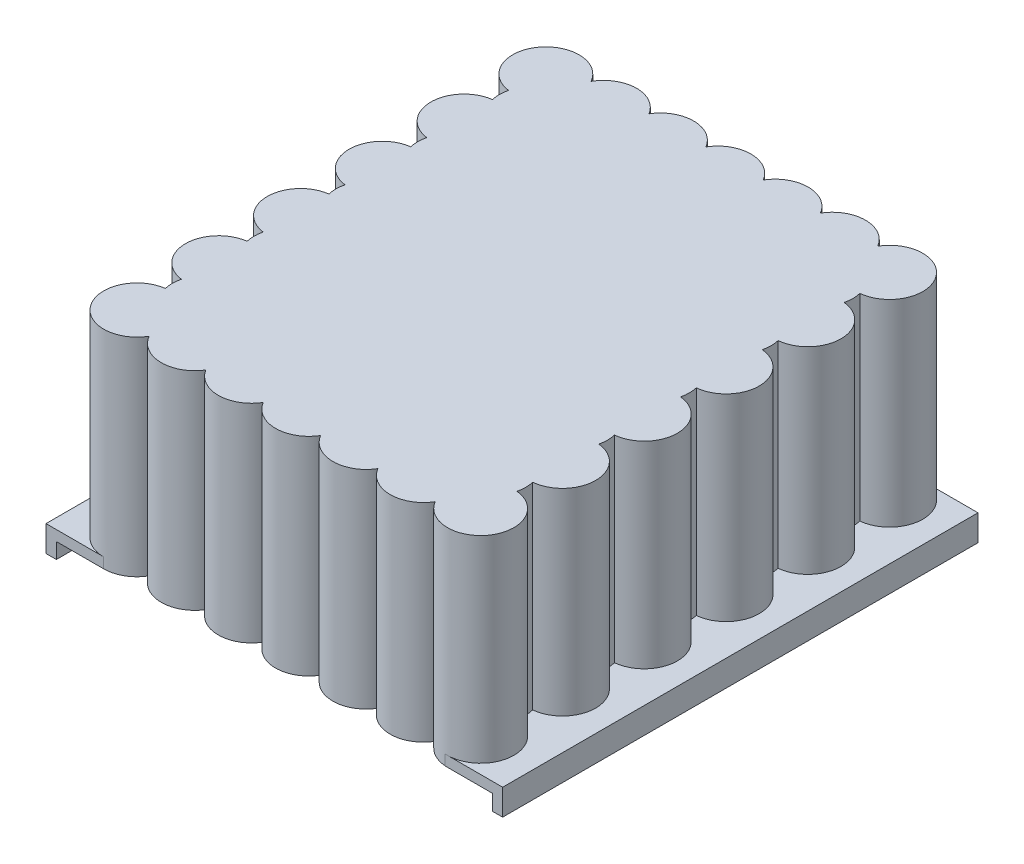
SolidWorks part; units mm, degrees
material "Titanium Ti-5Al-2.5Sn"
ref_plane "Front Plane" through (0, 0, 0) normal (0, 0, 1) x (1, 0, 0)
ref_plane "Top Plane" through (0, 0, 0) normal (0, 1, 0) x (1, 0, 0)
ref_plane "Right Plane" through (0, 0, 0) normal (1, 0, 0) x (0, 0, -1)
sketch "Sketch2" plane through (0, 0, 0) normal (0, 1, 0) x (1, 0, 0)
  circle A0 centre (-104.3845, 125.3413) radius 14
  circle A1 centre (-69.3845, 125.3413) radius 14
  circle A2 centre (-34.3845, 125.3413) radius 14
  circle A3 centre (0.6155, 125.3413) radius 14
  circle A4 centre (35.6155, 125.3413) radius 14
  circle A5 centre (70.6155, 125.3413) radius 14
  circle A6 centre (105.6155, 125.3413) radius 14
  circle A7 centre (-69.3845, 75.3413) radius 14
  circle A8 centre (-34.3845, 75.3413) radius 14
  circle A9 centre (0.6155, 75.3413) radius 14
  circle A10 centre (35.6155, 75.3413) radius 14
  circle A11 centre (70.6155, 75.3413) radius 14
  circle A12 centre (105.6155, 75.3413) radius 14
  circle A13 centre (-69.3845, 25.3413) radius 14
  circle A14 centre (-34.3845, 25.3413) radius 14
  circle A15 centre (0.6155, 25.3413) radius 14
  circle A16 centre (35.6155, 25.3413) radius 14
  circle A17 centre (70.6155, 25.3413) radius 14
  circle A18 centre (105.6155, 25.3413) radius 14
  circle A19 centre (-69.3845, -24.6587) radius 14
  circle A20 centre (-34.3845, -24.6587) radius 14
  circle A21 centre (0.6155, -24.6587) radius 14
  circle A22 centre (35.6155, -24.6587) radius 14
  circle A23 centre (70.6155, -24.6587) radius 14
  circle A24 centre (105.6155, -24.6587) radius 14
  circle A25 centre (-69.3845, -74.6587) radius 14
  circle A26 centre (-34.3845, -74.6587) radius 14
  circle A27 centre (0.6155, -74.6587) radius 14
  circle A28 centre (35.6155, -74.6587) radius 14
  circle A29 centre (70.6155, -74.6587) radius 14
  circle A30 centre (105.6155, -74.6587) radius 14
  circle A31 centre (-69.3845, -124.6587) radius 14
  circle A32 centre (-34.3845, -124.6587) radius 14
  circle A33 centre (0.6155, -124.6587) radius 14
  circle A34 centre (35.6155, -124.6587) radius 14
  circle A35 centre (70.6155, -124.6587) radius 14
  circle A36 centre (105.6155, -124.6587) radius 14
  circle A37 centre (-104.3845, 75.3413) radius 14
  circle A38 centre (-104.3845, 25.3413) radius 14
  circle A39 centre (-104.3845, -24.6587) radius 14
  circle A40 centre (-104.3845, -74.6587) radius 14
  circle A41 centre (-104.3845, -124.6587) radius 14
  circle A42 centre (-87.3845, 100.3413) radius 14
  circle A43 centre (-52.3845, 100.3413) radius 14
  circle A44 centre (-17.3845, 100.3413) radius 14
  circle A45 centre (17.6155, 100.3413) radius 14
  circle A46 centre (52.6155, 100.3413) radius 14
  circle A47 centre (87.6155, 100.3413) radius 14
  circle A48 centre (-52.3845, 50.3413) radius 14
  circle A49 centre (-17.3845, 50.3413) radius 14
  circle A50 centre (17.6155, 50.3413) radius 14
  circle A51 centre (52.6155, 50.3413) radius 14
  circle A52 centre (87.6155, 50.3413) radius 14
  circle A53 centre (-52.3845, 0.3413) radius 14
  circle A54 centre (-17.3845, 0.3413) radius 14
  circle A55 centre (17.6155, 0.3413) radius 14
  circle A56 centre (52.6155, 0.3413) radius 14
  circle A57 centre (87.6155, 0.3413) radius 14
  circle A58 centre (-52.3845, -49.6587) radius 14
  circle A59 centre (-17.3845, -49.6587) radius 14
  circle A60 centre (17.6155, -49.6587) radius 14
  circle A61 centre (52.6155, -49.6587) radius 14
  circle A62 centre (87.6155, -49.6587) radius 14
  circle A63 centre (-52.3845, -99.6587) radius 14
  circle A64 centre (-17.3845, -99.6587) radius 14
  circle A65 centre (17.6155, -99.6587) radius 14
  circle A66 centre (52.6155, -99.6587) radius 14
  circle A67 centre (87.6155, -99.6587) radius 14
  circle A68 centre (-87.3845, 50.3413) radius 14
  circle A69 centre (-87.3845, 0.3413) radius 14
  circle A70 centre (-87.3845, -49.6587) radius 14
  circle A71 centre (-87.3845, -99.6587) radius 14
sketch "Sketch3" plane through (0, 0, 0) normal (0, 1, 0) x (1, 0, 0)
  line L1 (-132.3198, 152.7914) -> (134.3802, 152.7914)
  line L2 (-132.3198, 152.7914) -> (-132.3198, -152.0086)
  line L3 (-132.3198, -152.0086) -> (134.3802, -152.0086)
  line L4 (134.3802, 152.7914) -> (134.3802, -152.0086)
  dimension "D1" = 304.8
  dimension "D2" = 266.7
extrude "Boss-Extrude1" add sketch "Sketch3" along normal blind 127
extrude "Cut-Extrude1" cut sketch "Sketch2" along normal blind 101.6
sketch "Sketch4" plane through (0, 0, 0) normal (0, -1, 0) x (1, 0, 0)
  line L1 (-132.3198, 152.0086) -> (134.3802, 152.0086)
  line L2 (-132.3198, 152.0086) -> (-132.3198, -152.7914)
  line L3 (-132.3198, -152.7914) -> (134.3802, -152.7914)
  line L4 (134.3802, 152.0086) -> (134.3802, -152.7914)
  arc A0 (-86.7752, 134.7985) -> (-107.1138, 104.5229) centre (-104.3845, 124.6587) ccw
  arc A5 (-16.7545, 114.3757) -> (-1.7647, 104.4976) centre (0.7715, 124.6587) ccw
  arc A7 (51.1245, 119.8835) -> (90.6148, 119.8357) centre (70.8755, 124.6587) ccw
  arc A8 (86.1781, 119.8771) -> (88.4015, 114.3757) centre (105.9275, 124.6587) ccw
  arc A9 (-49.6103, 79.513) -> (-51.8065, 84.9038) centre (-69.3325, 74.6207) ccw
  arc A10 (-51.8065, 84.9038) -> (-54.0268, 79.4152) centre (-34.2805, 74.6207) ccw
  arc A12 (33.3518, 54.4516) -> (33.3609, 94.791) centre (35.8235, 74.6207) ccw
  circle A13 centre (70.8755, 74.6207) radius 20.32
  arc A14 (88.4015, 84.9038) -> (88.4015, 64.3377) centre (105.9275, 74.6207) ccw
  arc A15 (-86.8585, 14.2997) -> (-84.6553, 19.7186) centre (-104.3845, 24.5827) ccw
  arc A16 (-89.0802, 29.3716) -> (-49.6012, 19.7272) centre (-69.3325, 24.5827) ccw
  arc A19 (16.071, 19.8137) -> (37.7142, 44.8146) centre (35.8235, 24.5827) ccw
  circle A20 centre (70.8755, 24.5827) radius 20.32
  arc A21 (88.4015, 34.8658) -> (88.4015, 14.2997) centre (105.9275, 24.5827) ccw
  arc A22 (-86.8585, -35.7383) -> (-86.8585, -15.1722) centre (-104.3845, -25.4553) ccw
  circle A23 centre (-69.3325, -25.4553) radius 20.32
  circle A24 centre (-34.2805, -25.4553) radius 20.32
  circle A25 centre (0.7715, -25.4553) radius 20.32
  circle A26 centre (35.8235, -25.4553) radius 20.32
  arc A27 (90.6057, -20.5953) -> (88.4015, -35.7383) centre (70.8755, -25.4553) ccw
  arc A28 (88.4015, -15.1722) -> (88.4015, -35.7383) centre (105.9275, -25.4553) ccw
  arc A29 (-86.8585, -85.7763) -> (-86.8585, -65.2102) centre (-104.3845, -75.4933) ccw
  circle A30 centre (-69.3325, -75.4933) radius 20.32
  circle A31 centre (-34.2805, -75.4933) radius 20.32
  circle A32 centre (0.7715, -75.4933) radius 20.32
  circle A33 centre (35.8235, -75.4933) radius 20.32
  circle A34 centre (70.8755, -75.4933) radius 20.32
  arc A35 (88.4015, -65.2102) -> (88.4015, -85.7763) centre (105.9275, -75.4933) ccw
  arc A36 (-84.6644, -120.6304) -> (-86.6147, -115.6754) centre (-104.3845, -125.5313) ccw
  arc A37 (-49.4244, -120.6136) -> (-88.6164, -120.7759) centre (-69.0004, -125.5313) ccw
  arc A38 (-14.5562, -120.6473) -> (-54.0268, -120.7368) centre (-34.2805, -125.5313) ccw
  arc A39 (20.4978, -120.6555) -> (-18.9734, -120.7311) centre (0.7715, -125.5313) ccw
  arc A40 (55.5518, -120.6635) -> (16.08, -120.7251) centre (35.8235, -125.5313) ccw
  arc A41 (90.6057, -120.6713) -> (51.1336, -120.7189) centre (70.8755, -125.5313) ccw
  arc A42 (88.4015, -115.2482) -> (86.1871, -120.7126) centre (105.9275, -125.5313) ccw
  arc A43 (-107.1138, 104.5229) -> (-107.1047, 94.7578) centre (-87.3845, 99.6587) ccw
  arc A44 (-54.0268, 79.4152) -> (-34.7069, 89.4325) centre (-52.2661, 99.6587) ccw
  arc A47 (33.3609, 94.791) -> (35.53, 109.885) centre (53.0892, 99.6587) ccw
  arc A48 (90.6148, 119.8357) -> (90.6057, 79.4807) centre (88.2076, 99.6587) ccw
  arc A49 (-89.0802, 29.3716) -> (-84.6644, 29.4836) centre (-87.3845, 49.6207) ccw
  arc A50 (-69.8253, 59.847) -> (-71.9974, 54.4762) centre (-52.2661, 49.6207) ccw
  arc A51 (-34.7069, 59.847) -> (-36.8811, 54.4678) centre (-17.1477, 49.6207) ccw
  arc A52 (35.53, 39.3945) -> (33.3518, 54.4516) centre (53.0892, 49.6207) ccw
  arc A53 (90.6148, 69.7977) -> (90.6057, 29.4427) centre (88.2076, 49.6207) ccw
  arc A54 (20.4978, 29.4585) -> (35.53, 39.3945) centre (17.9708, 49.6207) ccw
  arc A55 (-89.0802, -20.6664) -> (-89.0891, 19.8311) centre (-87.3845, -0.4173) ccw
  circle A56 centre (-52.2661, -0.4173) radius 20.32
  arc A57 (-14.5471, 19.7356) -> (-18.9824, 19.8197) centre (-17.1477, -0.4173) ccw
  circle A58 centre (53.0892, -0.4173) radius 20.32
  arc A59 (90.6148, 19.7597) -> (90.6057, -20.5953) centre (88.2076, -0.4173) ccw
  circle A60 centre (17.9708, -0.4173) radius 20.32
  arc A61 (-89.0802, -70.7044) -> (-89.0891, -30.2069) centre (-87.3845, -50.4553) ccw
  circle A62 centre (-52.2661, -50.4553) radius 20.32
  circle A63 centre (-17.1477, -50.4553) radius 20.32
  circle A64 centre (53.0892, -50.4553) radius 20.32
  arc A65 (86.1781, -30.2369) -> (90.6057, -70.6333) centre (88.2076, -50.4553) ccw
  circle A66 centre (17.9708, -50.4553) radius 20.32
  arc A67 (-88.6164, -120.7759) -> (-89.0891, -80.2449) centre (-87.3845, -100.4933) ccw
  circle A68 centre (-52.2661, -100.4933) radius 20.32
  circle A69 centre (-17.1477, -100.4933) radius 20.32
  circle A70 centre (53.0892, -100.4933) radius 20.32
  arc A71 (90.6148, -80.3163) -> (90.6057, -120.6713) centre (88.2076, -100.4933) ccw
  circle A72 centre (17.9708, -100.4933) radius 20.32
  arc A74 (-89.0891, 119.9071) -> (-86.8585, 114.3757) centre (-69.3325, 124.6587) ccw
  arc A76 (-32.5108, 104.4159) -> (-34.7069, 109.885) centre (-52.2661, 99.6587) ccw
  arc A78 (-67.6279, 54.3724) -> (-69.8253, 59.847) centre (-87.3845, 49.6207) ccw
  arc A79 (-67.6369, 44.8319) -> (-71.9884, 44.7284) centre (-69.3325, 24.5827) ccw
  arc A80 (-49.6103, 29.475) -> (-51.8065, 34.8658) centre (-69.3325, 24.5827) ccw
  arc A81 (-1.7556, 94.783) -> (0.4116, 89.4325) centre (17.9708, 99.6587) ccw
  arc A82 (-34.7069, 109.885) -> (-36.8811, 104.5058) centre (-17.1477, 99.6587) ccw
  arc A83 (-54.0358, 19.8255) -> (-16.7545, 14.2997) centre (-34.2805, 24.5827) ccw
  arc A84 (-36.8811, 104.5058) -> (-32.5108, 104.4159) centre (-34.2805, 124.6587) ccw
  arc A85 (-51.5561, 135.3572) -> (-86.7752, 134.7985) centre (-69.0004, 124.6587) ccw
  arc A86 (-16.7545, 134.9418) -> (-51.5561, 135.3572) centre (-34.2805, 124.6587) ccw
  arc A87 (18.2975, 134.9418) -> (-16.7545, 134.9418) centre (0.7715, 124.6587) ccw
  arc A88 (53.3495, 134.9418) -> (18.2975, 134.9418) centre (35.8235, 124.6587) ccw
  arc A89 (88.4015, 134.9418) -> (53.3495, 134.9418) centre (70.8755, 124.6587) ccw
  arc A90 (107.957, 104.4403) -> (88.4015, 134.9418) centre (105.9275, 124.6587) ccw
  arc A91 (107.948, 94.84) -> (107.957, 104.4403) centre (88.2076, 99.6587) ccw
  arc A92 (107.957, 54.4023) -> (107.948, 94.84) centre (105.9275, 74.6207) ccw
  arc A93 (107.948, 44.802) -> (107.957, 54.4023) centre (88.2076, 49.6207) ccw
  arc A94 (107.957, 4.3643) -> (107.948, 44.802) centre (105.9275, 24.5827) ccw
  arc A95 (107.948, -5.236) -> (107.957, 4.3643) centre (88.2076, -0.4173) ccw
  arc A96 (107.957, -45.6737) -> (107.948, -5.236) centre (105.9275, -25.4553) ccw
  arc A97 (107.948, -55.274) -> (107.957, -45.6737) centre (88.2076, -50.4553) ccw
  arc A98 (107.957, -95.7117) -> (107.948, -55.274) centre (105.9275, -75.4933) ccw
  arc A99 (107.948, -105.312) -> (107.957, -95.7117) centre (88.2076, -100.4933) ccw
  arc A100 (88.4015, -135.8143) -> (107.948, -105.312) centre (105.9275, -125.5313) ccw
  arc A101 (53.3495, -135.8143) -> (88.4015, -135.8143) centre (70.8755, -125.5313) ccw
  arc A102 (18.2975, -135.8143) -> (53.3495, -135.8143) centre (35.8235, -125.5313) ccw
  arc A103 (-16.7545, -135.8143) -> (18.2975, -135.8143) centre (0.7715, -125.5313) ccw
  arc A104 (-51.7196, -135.961) -> (-16.7545, -135.8143) centre (-34.2805, -125.5313) ccw
  arc A105 (-86.6147, -135.3871) -> (-51.7196, -135.961) centre (-69.0004, -125.5313) ccw
  arc A106 (-107.1047, -105.3942) -> (-86.6147, -135.3871) centre (-104.3845, -125.5313) ccw
  arc A107 (-107.1138, -95.6291) -> (-107.1047, -105.3942) centre (-87.3845, -100.4933) ccw
  arc A108 (-107.1047, -55.3562) -> (-107.1138, -95.6291) centre (-104.3845, -75.4933) ccw
  arc A109 (-107.1138, -45.5911) -> (-107.1047, -55.3562) centre (-87.3845, -50.4553) ccw
  arc A110 (-107.1047, -5.3182) -> (-107.1138, -45.5911) centre (-104.3845, -25.4553) ccw
  arc A111 (-107.1138, 4.4469) -> (-107.1047, -5.3182) centre (-87.3845, -0.4173) ccw
  arc A112 (-107.1047, 44.7198) -> (-107.1138, 4.4469) centre (-104.3845, 24.5827) ccw
  arc A113 (-107.1138, 54.4849) -> (-107.1047, 44.7198) centre (-87.3845, 49.6207) ccw
  arc A114 (-34.7069, 9.809) -> (0.4116, 9.809) centre (-17.1477, -0.4173) ccw
  arc A115 (-107.1047, 94.7578) -> (-107.1138, 54.4849) centre (-104.3845, 74.6207) ccw
  arc A116 (-16.7545, 114.3757) -> (-14.5471, 119.8116) centre (-34.2805, 124.6587) ccw
  arc A117 (0.4116, 109.885) -> (-1.7647, 104.4976) centre (17.9708, 99.6587) ccw
  arc A119 (37.7232, 104.4277) -> (55.5609, 119.8278) centre (35.8235, 124.6587) ccw
  arc A120 (-34.7069, 89.4325) -> (-18.9734, 79.4209) centre (-17.1477, 99.6587) ccw
  arc A122 (20.5069, 69.7818) -> (20.4978, 79.4965) centre (0.7715, 74.6207) ccw
  arc A124 (-14.5471, 69.7736) -> (-18.9824, 69.8577) centre (-17.1477, 49.6207) ccw
  arc A125 (-54.0358, 69.8635) -> (-32.5108, 54.3779) centre (-34.2805, 74.6207) ccw
  arc A127 (-71.9974, 54.4762) -> (-67.6279, 54.3724) centre (-69.3325, 74.6207) ccw
  arc A132 (-86.8585, 64.3377) -> (-84.6553, 69.7566) centre (-104.3845, 74.6207) ccw
  arc A133 (-51.8065, 64.3377) -> (-49.6012, 69.7652) centre (-69.3325, 74.6207) ccw
  arc A134 (-18.9734, 29.3829) -> (-14.5562, 29.4667) centre (-17.1477, 49.6207) ccw
  arc A135 (-32.5108, 54.3779) -> (-54.0358, 69.8635) centre (-52.2661, 49.6207) ccw
  arc A137 (37.7142, 44.8146) -> (35.53, 59.847) centre (17.9708, 49.6207) ccw
  arc A139 (33.3609, 44.753) -> (18.2975, 34.8658) centre (35.8235, 24.5827) ccw
  arc A140 (-16.7545, 14.2997) -> (20.4978, 29.4585) centre (0.7715, 24.5827) ccw
  arc A141 (20.5069, 69.7818) -> (-1.7647, 54.4596) centre (17.9708, 49.6207) ccw
  arc A142 (35.53, 89.4325) -> (37.7232, 104.4277) centre (17.9708, 99.6587) ccw
  arc A145 (-18.9824, 69.8577) -> (-16.7545, 64.3377) centre (0.7715, 74.6207) ccw
  arc A146 (16.08, 79.4269) -> (20.4978, 79.4965) centre (17.9708, 99.6587) ccw
  arc A148 (16.071, 119.8897) -> (18.2975, 114.3757) centre (35.8235, 124.6587) ccw
  arc A149 (-16.7545, 34.8658) -> (-18.9734, 29.3829) centre (0.7715, 24.5827) ccw
  dimension "D1" = 40.64
  dimension "D2" = 7
  dimension "D4" = 40.64
  dimension "D3" = 6
  dimension "D5" = 6
  dimension "D6" = 5
sketch "Sketch5" plane through (0, 0, 0) normal (0, -1, 0) x (1, 0, 0)
  line L0 (-132.3198, 152.0086) -> (-132.3198, -152.7914) construction
  line L1 (-132.3198, -152.7914) -> (134.3802, -152.7914) construction
  line L2 (134.3802, 152.0086) -> (134.3802, -152.7914) construction
  line L3 (-132.3198, 152.0086) -> (134.3802, 152.0086) construction
  line L4 (-132.3198, 152.0086) -> (-132.3198, -152.7914)
  line L5 (-132.3198, -152.7914) -> (134.3802, -152.7914)
  line L6 (134.3802, 152.0086) -> (134.3802, -152.7914)
  line L7 (-132.3198, 152.0086) -> (134.3802, 152.0086)
  arc A0 (-86.7752, 134.7985) -> (-107.1138, 104.5229) centre (-104.3845, 124.6587) ccw construction
  arc A1 (-107.1138, 104.5229) -> (-107.1047, 94.7578) centre (-87.3845, 99.6587) ccw construction
  arc A2 (-107.1047, 94.7578) -> (-107.1138, 54.4849) centre (-104.3845, 74.6207) ccw construction
  arc A3 (-107.1138, 54.4849) -> (-107.1047, 44.7198) centre (-87.3845, 49.6207) ccw construction
  arc A4 (-107.1047, 44.7198) -> (-107.1138, 4.4469) centre (-104.3845, 24.5827) ccw construction
  arc A5 (-107.1138, 4.4469) -> (-107.1047, -5.3182) centre (-87.3845, -0.4173) ccw construction
  arc A6 (-107.1047, -5.3182) -> (-107.1138, -45.5911) centre (-104.3845, -25.4553) ccw construction
  arc A7 (-107.1138, -45.5911) -> (-107.1047, -55.3562) centre (-87.3845, -50.4553) ccw construction
  arc A8 (-107.1047, -55.3562) -> (-107.1138, -95.6291) centre (-104.3845, -75.4933) ccw construction
  arc A9 (-107.1138, -95.6291) -> (-107.1047, -105.3942) centre (-87.3845, -100.4933) ccw construction
  arc A10 (-107.1047, -105.3942) -> (-86.6147, -135.3871) centre (-104.3845, -125.5313) ccw construction
  arc A11 (-86.6147, -135.3871) -> (-51.7196, -135.961) centre (-69.0004, -125.5313) ccw construction
  arc A12 (-51.7196, -135.961) -> (-16.7545, -135.8143) centre (-34.2805, -125.5313) ccw construction
  arc A13 (-16.7545, -135.8143) -> (18.2975, -135.8143) centre (0.7715, -125.5313) ccw construction
  arc A14 (18.2975, -135.8143) -> (53.3495, -135.8143) centre (35.8235, -125.5313) ccw construction
  arc A15 (53.3495, -135.8143) -> (88.4015, -135.8143) centre (70.8755, -125.5313) ccw construction
  arc A16 (88.4015, -135.8143) -> (107.948, -105.312) centre (105.9275, -125.5313) ccw construction
  arc A17 (107.948, -105.312) -> (107.957, -95.7117) centre (88.2076, -100.4933) ccw construction
  arc A18 (107.957, -95.7117) -> (107.948, -55.274) centre (105.9275, -75.4933) ccw construction
  arc A19 (107.948, -55.274) -> (107.957, -45.6737) centre (88.2076, -50.4553) ccw construction
  arc A20 (107.957, -45.6737) -> (107.948, -5.236) centre (105.9275, -25.4553) ccw construction
  arc A21 (107.948, -5.236) -> (107.957, 4.3643) centre (88.2076, -0.4173) ccw construction
  arc A22 (107.957, 4.3643) -> (107.948, 44.802) centre (105.9275, 24.5827) ccw construction
  arc A23 (107.948, 44.802) -> (107.957, 54.4023) centre (88.2076, 49.6207) ccw construction
  arc A24 (107.957, 54.4023) -> (107.948, 94.84) centre (105.9275, 74.6207) ccw construction
  arc A25 (107.948, 94.84) -> (107.957, 104.4403) centre (88.2076, 99.6587) ccw construction
  arc A26 (107.957, 104.4403) -> (88.4015, 134.9418) centre (105.9275, 124.6587) ccw construction
  arc A27 (88.4015, 134.9418) -> (53.3495, 134.9418) centre (70.8755, 124.6587) ccw construction
  arc A28 (53.3495, 134.9418) -> (18.2975, 134.9418) centre (35.8235, 124.6587) ccw construction
  arc A29 (18.2975, 134.9418) -> (-16.7545, 134.9418) centre (0.7715, 124.6587) ccw construction
  arc A30 (-16.7545, 134.9418) -> (-51.5561, 135.3572) centre (-34.2805, 124.6587) ccw construction
  arc A31 (-51.5561, 135.3572) -> (-86.7752, 134.7985) centre (-69.0004, 124.6587) ccw construction
  arc A32 (-86.7752, 134.7985) -> (-107.1138, 104.5229) centre (-104.3845, 124.6587) ccw
  arc A33 (-107.1138, 104.5229) -> (-107.1047, 94.7578) centre (-87.3845, 99.6587) ccw
  arc A34 (-107.1047, 94.7578) -> (-107.1138, 54.4849) centre (-104.3845, 74.6207) ccw
  arc A35 (-107.1138, 54.4849) -> (-107.1047, 44.7198) centre (-87.3845, 49.6207) ccw
  arc A36 (-107.1047, 44.7198) -> (-107.1138, 4.4469) centre (-104.3845, 24.5827) ccw
  arc A37 (-107.1138, 4.4469) -> (-107.1047, -5.3182) centre (-87.3845, -0.4173) ccw
  arc A38 (-107.1047, -5.3182) -> (-107.1138, -45.5911) centre (-104.3845, -25.4553) ccw
  arc A39 (-107.1138, -45.5911) -> (-107.1047, -55.3562) centre (-87.3845, -50.4553) ccw
  arc A40 (-107.1047, -55.3562) -> (-107.1138, -95.6291) centre (-104.3845, -75.4933) ccw
  arc A41 (-107.1138, -95.6291) -> (-107.1047, -105.3942) centre (-87.3845, -100.4933) ccw
  arc A42 (-107.1047, -105.3942) -> (-86.6147, -135.3871) centre (-104.3845, -125.5313) ccw
  arc A43 (-86.6147, -135.3871) -> (-51.7196, -135.961) centre (-69.0004, -125.5313) ccw
  arc A44 (-51.7196, -135.961) -> (-16.7545, -135.8143) centre (-34.2805, -125.5313) ccw
  arc A45 (-16.7545, -135.8143) -> (18.2975, -135.8143) centre (0.7715, -125.5313) ccw
  arc A46 (18.2975, -135.8143) -> (53.3495, -135.8143) centre (35.8235, -125.5313) ccw
  arc A47 (53.3495, -135.8143) -> (88.4015, -135.8143) centre (70.8755, -125.5313) ccw
  arc A48 (88.4015, -135.8143) -> (107.948, -105.312) centre (105.9275, -125.5313) ccw
  arc A49 (107.948, -105.312) -> (107.957, -95.7117) centre (88.2076, -100.4933) ccw
  arc A50 (107.957, -95.7117) -> (107.948, -55.274) centre (105.9275, -75.4933) ccw
  arc A51 (107.948, -55.274) -> (107.957, -45.6737) centre (88.2076, -50.4553) ccw
  arc A52 (107.957, -45.6737) -> (107.948, -5.236) centre (105.9275, -25.4553) ccw
  arc A53 (107.948, -5.236) -> (107.957, 4.3643) centre (88.2076, -0.4173) ccw
  arc A54 (107.957, 4.3643) -> (107.948, 44.802) centre (105.9275, 24.5827) ccw
  arc A55 (107.948, 44.802) -> (107.957, 54.4023) centre (88.2076, 49.6207) ccw
  arc A56 (107.957, 54.4023) -> (107.948, 94.84) centre (105.9275, 74.6207) ccw
  arc A57 (107.948, 94.84) -> (107.957, 104.4403) centre (88.2076, 99.6587) ccw
  arc A58 (107.957, 104.4403) -> (88.4015, 134.9418) centre (105.9275, 124.6587) ccw
  arc A59 (88.4015, 134.9418) -> (53.3495, 134.9418) centre (70.8755, 124.6587) ccw
  arc A60 (53.3495, 134.9418) -> (18.2975, 134.9418) centre (35.8235, 124.6587) ccw
  arc A61 (18.2975, 134.9418) -> (-16.7545, 134.9418) centre (0.7715, 124.6587) ccw
  arc A62 (-16.7545, 134.9418) -> (-51.5561, 135.3572) centre (-34.2805, 124.6587) ccw
  arc A63 (-51.5561, 135.3572) -> (-86.7752, 134.7985) centre (-69.0004, 124.6587) ccw
extrude "Cut-Extrude2" cut sketch "Sketch5" against normal through all
sketch "Sketch6" plane through (0, 0, 0) normal (0, -1, 0) x (1, 0, 0)
  line L0 (-104.3845, 144.9787) -> (-139.7, 144.9787)
  line L1 (-139.7, 144.9787) -> (-139.7, -145.8513)
  line L2 (-104.3845, -145.8513) -> (-139.7, -145.8513)
  line L3 (0, -69.85) -> (0, 69.85) construction
  arc A0 (-107.1047, -105.3942) -> (-86.6147, -135.3871) centre (-104.3845, -125.5313) ccw construction
  arc A1 (-107.1138, -95.6291) -> (-107.1047, -105.3942) centre (-87.3845, -100.4933) ccw construction
  arc A2 (-107.1047, -55.3562) -> (-107.1138, -95.6291) centre (-104.3845, -75.4933) ccw construction
  arc A3 (-107.1138, -45.5911) -> (-107.1047, -55.3562) centre (-87.3845, -50.4553) ccw construction
  arc A4 (-107.1047, -5.3182) -> (-107.1138, -45.5911) centre (-104.3845, -25.4553) ccw construction
  arc A5 (-107.1138, 4.4469) -> (-107.1047, -5.3182) centre (-87.3845, -0.4173) ccw construction
  arc A6 (-107.1047, 44.7198) -> (-107.1138, 4.4469) centre (-104.3845, 24.5827) ccw construction
  arc A7 (-107.1138, 54.4849) -> (-107.1047, 44.7198) centre (-87.3845, 49.6207) ccw construction
  arc A8 (-107.1047, 94.7578) -> (-107.1138, 54.4849) centre (-104.3845, 74.6207) ccw construction
  arc A9 (-107.1138, 104.5229) -> (-107.1047, 94.7578) centre (-87.3845, 99.6587) ccw construction
  arc A10 (-86.7752, 134.7985) -> (-107.1138, 104.5229) centre (-104.3845, 124.6587) ccw construction
  arc A11 (-107.1047, -105.3942) -> (-104.3845, -145.8513) centre (-104.3845, -125.5313) ccw
  arc A12 (-107.1138, -95.6291) -> (-107.1047, -105.3942) centre (-87.3845, -100.4933) ccw
  arc A13 (-107.1047, -55.3562) -> (-107.1138, -95.6291) centre (-104.3845, -75.4933) ccw
  arc A14 (-107.1138, -45.5911) -> (-107.1047, -55.3562) centre (-87.3845, -50.4553) ccw
  arc A15 (-107.1047, -5.3182) -> (-107.1138, -45.5911) centre (-104.3845, -25.4553) ccw
  arc A16 (-107.1138, 4.4469) -> (-107.1047, -5.3182) centre (-87.3845, -0.4173) ccw
  arc A17 (-107.1047, 44.7198) -> (-107.1138, 4.4469) centre (-104.3845, 24.5827) ccw
  arc A18 (-107.1138, 54.4849) -> (-107.1047, 44.7198) centre (-87.3845, 49.6207) ccw
  arc A19 (-107.1047, 94.7578) -> (-107.1138, 54.4849) centre (-104.3845, 74.6207) ccw
  arc A20 (-107.1138, 104.5229) -> (-107.1047, 94.7578) centre (-87.3845, 99.6587) ccw
  arc A21 (-104.3845, 144.9787) -> (-107.1138, 104.5229) centre (-104.3845, 124.6587) ccw
  dimension "D1" = 139.7
extrude "Boss-Extrude2" add sketch "Sketch6" against normal blind 6.35
mirror "Mirror2" about plane through (0, 0, 0) normal (1, 0, 0) of "Boss-Extrude2"
ref_plane "Plane1" through (0, 0, -145.8513) normal (0, 0, -1) x (-1, 0, 0)
sketch "Sketch7" plane through (0, 0, -145.8513) normal (0, 0, -1) x (-1, 0, 0)
  line L1 (-44.45, 88.9) -> (44.45, 88.9)
  line L2 (-44.45, 88.9) -> (-44.45, 25.4)
  line L3 (-44.45, 25.4) -> (44.45, 25.4)
  line L4 (44.45, 88.9) -> (44.45, 25.4)
  dimension "D1" = 44.45
  dimension "D2" = 88.9
  dimension "D3" = 25.4
  dimension "D4" = 63.5
extrude "Boss-Extrude4" add sketch "Sketch7" along normal blind 6.35 separate body
fillet "Fillet1" [suppressed] radius 2.54
fillet "Fillet2" [suppressed] radius 2.54
sketch "Sketch10" plane through (0, 0, 0) normal (0, -1, 0) x (1, 0, 0)
  line L0 (-104.3845, 144.9787) -> (-139.7, 144.9787) construction
  line L1 (-139.7, -145.8513) -> (-133.35, -145.8513)
  line L2 (-139.7, -145.8513) -> (-139.7, 144.9787)
  line L3 (-139.7, 144.9787) -> (-133.35, 144.9787)
  line L4 (-133.35, -145.8513) -> (-133.35, 144.9787)
  dimension "D1" = 6.35
extrude "Boss-Extrude5" add sketch "Sketch10" along normal blind 9.525
mirror "Mirror3" about plane through (0, 0, 0) normal (1, 0, 0) of "Boss-Extrude5"
